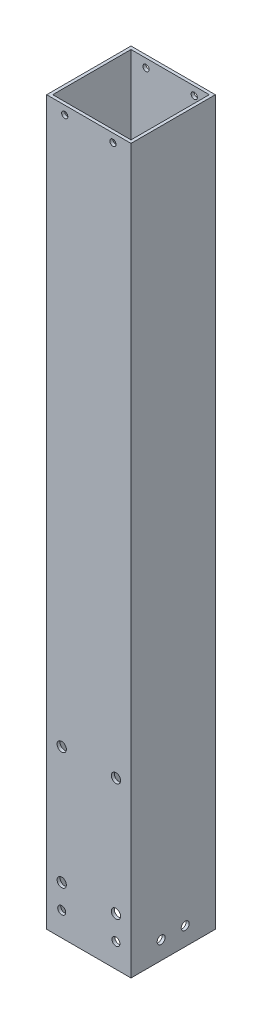
SolidWorks part; units mm, degrees
material "6061-T6 (SS)"
ref_plane "Front Plane" through (0, 0, 0) normal (0, 0, 1) x (1, 0, 0)
ref_plane "Top Plane" through (0, 0, 0) normal (0, 1, 0) x (1, 0, 0)
ref_plane "Right Plane" through (0, 0, 0) normal (1, 0, 0) x (0, 0, -1)
sketch "Sketch1" plane through (0, 0, 0) normal (0, 1, 0) x (1, 0, 0)
  line L1 (44.45, 44.45) -> (-44.45, 44.45)
  line L2 (44.45, 44.45) -> (44.45, -44.45)
  line L3 (44.45, -44.45) -> (-44.45, -44.45)
  line L4 (-44.45, 44.45) -> (-44.45, -44.45)
  line L5 (44.45, 44.45) -> (-44.45, -44.45) construction
  line L6 (44.45, -44.45) -> (-44.45, 44.45) construction
  line L7 (41.275, -41.275) -> (-41.275, -41.275)
  line L8 (41.275, -41.275) -> (41.275, 41.275)
  line L9 (41.275, 41.275) -> (-41.275, 41.275)
  line L10 (-41.275, -41.275) -> (-41.275, 41.275)
  line L11 (41.275, -41.275) -> (-41.275, 41.275) construction
  line L12 (41.275, 41.275) -> (-41.275, -41.275) construction
  point P0 (0, 0)
  point P6 (0, 0)
  dimension "D1" = 88.9
  dimension "D2" = 3.175
extrude "Boss-Extrude1" add sketch "Sketch1" along normal blind 762
sketch "Sketch2" plane through (0, 0, 0) normal (0, 0, 1) x (1, 0, 0)
  line L0 (-44.45, 0) -> (44.45, 0) construction
  line L1 (28.575, 25.4) -> (-28.575, 25.4) construction
  circle A0 centre (-28.575, 25.4) radius 4.2164
  circle A1 centre (28.575, 25.4) radius 4.2164
  point P6 (0, 25.4)
  dimension "D3" = 8.4328
  dimension "D1" = 25.4
  dimension "D2" = 57.15
extrude "Cut-Extrude1" cut sketch "Sketch2" against normal through all both and the other way through all
sketch "Sketch3" plane through (-44.45, 0, 0) normal (-1, 0, 0) x (0, 0, 1)
  line L0 (12.7, 19.05) -> (-12.7, 19.05) construction
  circle A0 centre (0, -13.0095) radius 8.1915
  circle A1 centre (12.7, 19.05) radius 4.2164
  circle A2 centre (-12.7, 19.05) radius 4.2164
  point P6 (0, 19.05)
  dimension "D1" = 16.383
  dimension "D2" = 8.4328
  dimension "D3" = 19.05
  dimension "D4" = 25.4
extrude "Cut-Extrude2" cut sketch "Sketch3" against normal through all both and the other way through all
sketch "Sketch4" plane through (0, 0, -44.45) normal (0, 0, -1) x (-1, 0, 0)
  circle A0 centre (0, -2.54) radius 8.1915
  dimension "D1" = 16.383
  dimension "D2" = 2.54
extrude "Cut-Extrude3" cut sketch "Sketch4" against normal up to next and the other way through all
hole_wizard "3/8 Clearance Hole1" positions "3DSketch1" profile "Sketch7" hole size "3/8" standard "ANSI Inch"
sketch3d "3DSketch1"
  line L1 (0, 50.8, -44.45) -> (0, 190.5, -44.45) construction
  line L2 (44.45, 762, -44.45) -> (44.45, 0, -44.45) construction
  line L3 (-7.7878, 0, -44.45) -> (-44.45, 0, -44.45) construction
  point P0 (0, 50.8, -44.45)
  point P2 (0, 120.65, -44.45)
  point P4 (0, 190.5, -44.45)
  point P21 (0, 120.65, -44.45)
  dimension "D1" = 69.85
  dimension "D3" = 44.45
  dimension "D4" = 50.8
sketch "Sketch7" plane through (0, 50.8, -44.45) normal (1, 0, 0) x (0, 1, 0)
  line L0 (0, 0) -> (0, 88.9)
  line L1 (0, 88.9) -> (4.9022, 88.9)
  line L2 (4.9022, 88.9) -> (4.9022, 0)
  line L5 (4.9022, 0) -> (0, 0)
  line L11 (0, -6.35) -> (0, 107.95) construction
  dimension "Thru Hole Dia." = 9.8044
  dimension "Thru Hole Depth" = 88.9
sketch "Sketch8" plane through (0, 0, -44.45) normal (0, 0, -1) x (-1, 0, 0)
  line L1 (-28.575, 174.625) -> (28.575, 174.625)
  line L2 (-28.575, 174.625) -> (-28.575, 50.8)
  line L3 (-28.575, 50.8) -> (28.575, 50.8)
  line L4 (28.575, 174.625) -> (28.575, 50.8)
  line L5 (-28.575, 174.625) -> (28.575, 50.8) construction
  line L6 (-28.575, 50.8) -> (28.575, 174.625) construction
  point P8 (0, 174.625)
  point P11 (-28.575, 174.625)
  point P14 (28.575, 174.625)
  point P17 (28.575, 50.8)
  point P20 (-28.575, 50.8)
  dimension "D1" = 57.15
  dimension "D2" = 123.825
  dimension "D3" = 50.8
hole_wizard "3/8 Clearance Hole2" positions "3DSketch2" profile "Sketch9" hole size "3/8" standard "ANSI Inch" end condition through all
sketch3d "3DSketch2"
  point P0 (28.575, 50.8, -44.45)
  point P3 (-28.575, 50.8, -44.45)
  point P6 (-28.575, 174.625, -44.45)
  point P9 (28.575, 174.625, -44.45)
sketch "Sketch9" plane through (28.575, 50.8, -44.45) normal (1, 0, 0) x (0, 1, 0)
  line L0 (0, 0) -> (0, 88.9)
  line L1 (0, 88.9) -> (4.9022, 88.9)
  line L2 (4.9022, 88.9) -> (4.9022, 0)
  line L5 (4.9022, 0) -> (0, 0)
  line L11 (0, -6.35) -> (0, 107.95) construction
  dimension "Thru Hole Dia." = 9.8044
  dimension "Thru Hole Depth" = 88.9
sketch "Sketch10" plane through (0, 0, -44.45) normal (0, 0, -1) x (-1, 0, 0)
  circle A0 centre (0, 383.9845) radius 7.9375
  arc A1 (7.7878, 0) -> (-7.7878, 0) centre (0, -2.54) ccw construction
  dimension "D1" = 15.875
  dimension "D2" = 386.5245
extrude "Cut-Extrude4" cut sketch "Sketch10" against normal blind 8.128
sketch "Sketch11" plane through (0, 0, -44.45) normal (0, 0, -1) x (-1, 0, 0)
  line L0 (-25.4, 753.11) -> (25.4, 753.11) construction
  line L1 (-44.45, 762) -> (44.45, 762) construction
  point P4 (0, 762)
  point P5 (0, 753.11)
  point P6 (-25.4, 753.11)
  point P8 (25.4, 753.11)
  dimension "D1" = 8.89
  dimension "D2" = 50.8
hole_wizard "1/4 Clearance Hole1" positions "Sketch11" profile "Sketch12" hole size "1/4" standard "ANSI Inch" end condition through all
sketch "Sketch12" plane through (-25.4, 753.11, -44.45) normal (1, 0, 0) x (0, 1, 0)
  line L0 (0, 0) -> (0, 88.9)
  line L1 (0, 88.9) -> (3.2639, 88.9)
  line L2 (3.2639, 88.9) -> (3.2639, 0)
  line L5 (3.2639, 0) -> (0, 0)
  line L11 (0, -6.35) -> (0, 107.95) construction
  dimension "Thru Hole Dia." = 6.5278
  dimension "Thru Hole Depth" = 88.9
